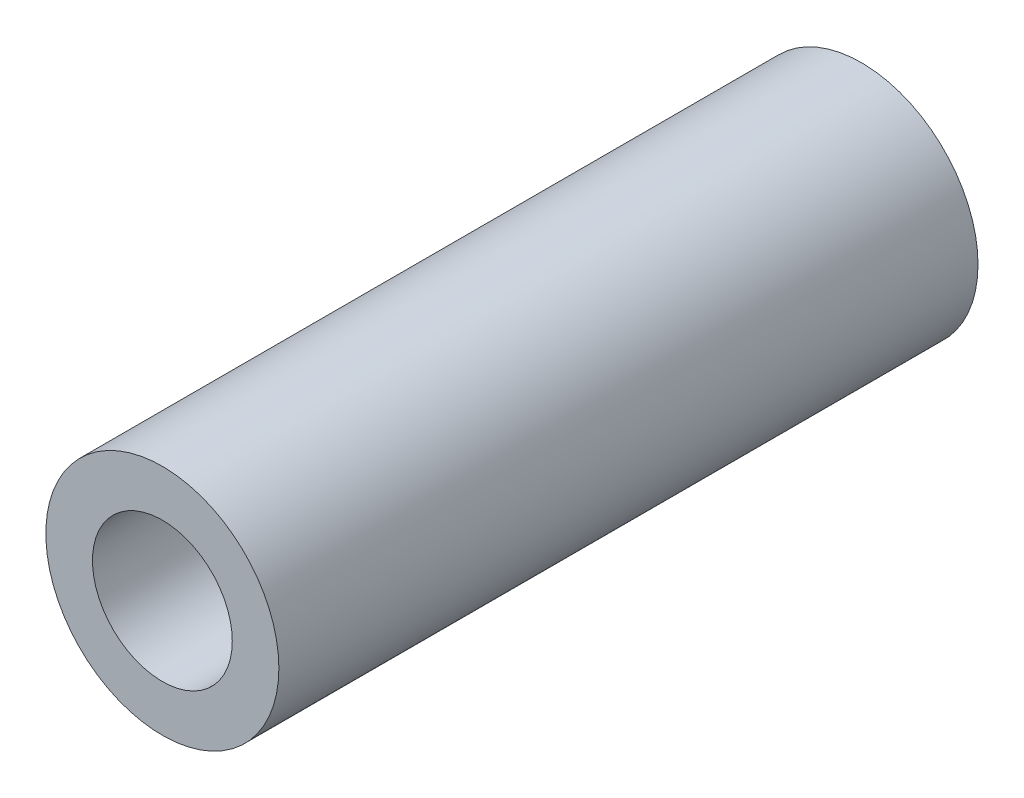
SolidWorks part; units mm, degrees
material "6061 Alloy"
ref_plane "Front Plane" through (0, 0, 0) normal (0, 0, 1) x (1, 0, 0)
ref_plane "Top Plane" through (0, 0, 0) normal (0, 1, 0) x (1, 0, 0)
ref_plane "Right Plane" through (0, 0, 0) normal (1, 0, 0) x (0, 0, -1)
sketch "Sketch1" plane through (0, 0, 0) normal (0, 0, 1) x (1, 0, 0)
  circle A0 centre (-25.0329, 16.5335) radius 2.5
  circle A1 centre (-25.0329, 16.5335) radius 1.5
  dimension "D1" = 3
  dimension "D2" = 5
extrude "Boss-Extrude1" add sketch "Sketch1" along normal blind 15
